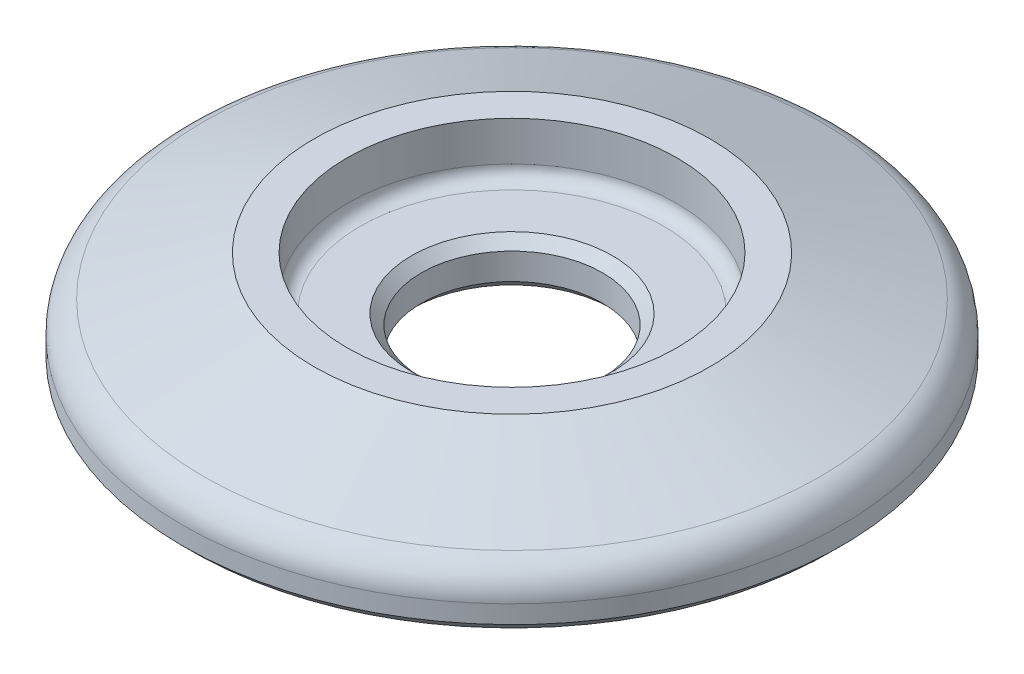
SolidWorks part; units mm, degrees
ref_plane "Front Plane" through (0, 0, 0) normal (0, 0, 1) x (1, 0, 0)
ref_plane "Top Plane" through (0, 0, 0) normal (0, 1, 0) x (1, 0, 0)
ref_plane "Right Plane" through (0, 0, 0) normal (1, 0, 0) x (0, 0, -1)
sketch "Sketch1" plane through (0, 0, 0) normal (0, 0, 1) x (1, 0, 0)
  line L0 (0, 0) -> (0, 8.0852) construction
  line L1 (2.75, 0) -> (2.75, 1.4)
  line L2 (2.75, 1.4) -> (5, 1.4)
  line L3 (5, 1.4) -> (5, 3)
  line L4 (5, 3) -> (6, 3)
  line L5 (6, 3) -> (10, 1.5441)
  line L6 (10, 1.5441) -> (10, 0)
  line L7 (10, 0) -> (2.75, 0)
  dimension "D1" = 5.5
  dimension "D2" = 10
  dimension "D3" = 1.4
  dimension "D4" = 3
  dimension "D5" = 1
  dimension "D6" = 20
  dimension "D7" = 20
revolve "Revolve1" add sketch "Sketch1" angle 360 about L0
fillet "Fillet2" radius 1 1 edges at (0, 1.5441, -10)
fillet "Fillet3" radius 0.4 1 edges at (0, 1.4, -5)
chamfer "Chamfer1" distance 0.3 angle 45 3 edges at (0, 1.4, -2.75) (0, 0, -2.75) (0, 0, -10)
